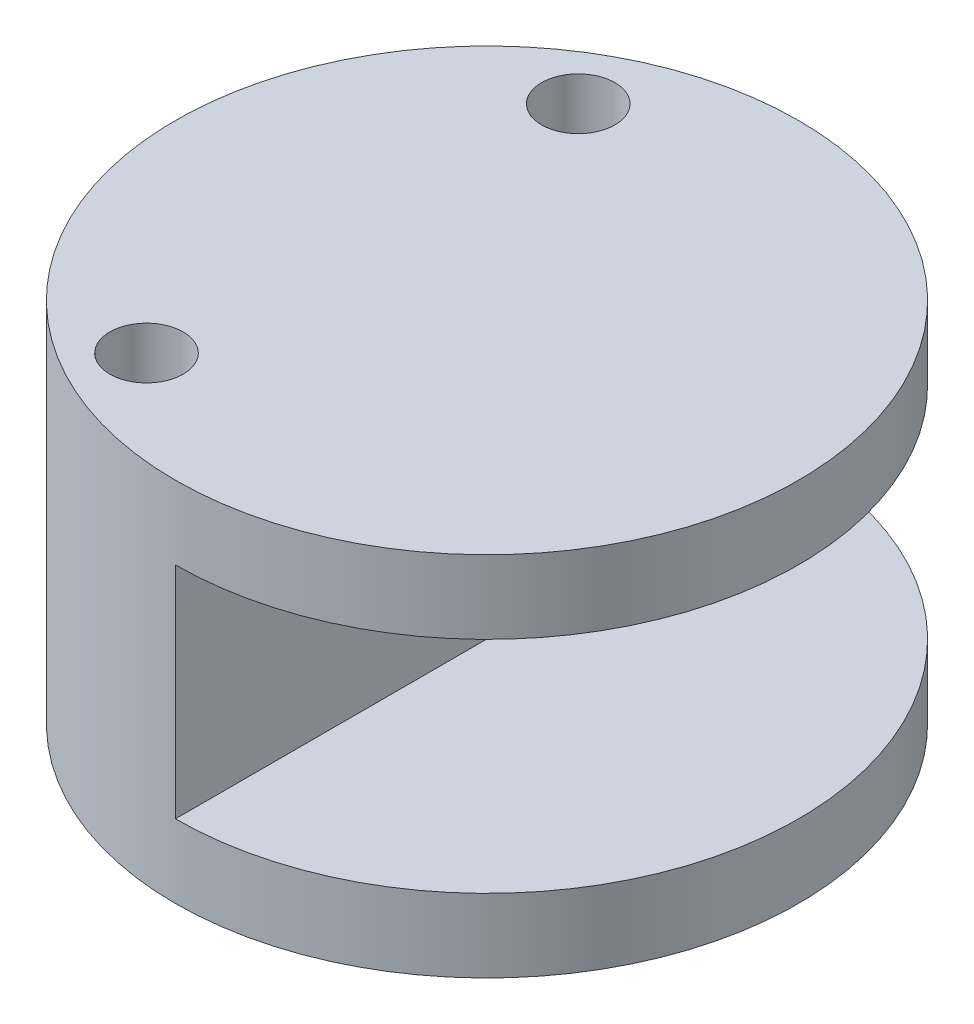
SolidWorks part; units mm, degrees
ref_plane "Front Plane" through (0, 0, 0) normal (0, 0, 1) x (1, 0, 0)
ref_plane "Top Plane" through (0, 0, 0) normal (0, 1, 0) x (1, 0, 0)
ref_plane "Right Plane" through (0, 0, 0) normal (1, 0, 0) x (0, 0, -1)
sketch "Sketch1" plane through (0, 0, 0) normal (0, 1, 0) x (1, 0, 0)
  circle A0 centre (0, 0) radius 12.7
  dimension "D1" = 25.4
sketch "Sketch2" plane through (0, 0, 0) normal (0, 1, 0) x (1, 0, 0)
  circle A0 centre (0, 0) radius 10.795
  dimension "D1" = 21.59
extrude "Boss-Extrude1" add sketch "Sketch2" against normal blind 12.7
sketch "Sketch3" plane through (0, 0, 0) normal (1, 0, 0) x (0, 0, -1)
  line L0 (12.7, 0) -> (-12.7, 0) construction
  line L1 (-13.6481, -2.54) -> (11.7912, -2.54)
  line L2 (-13.6481, -2.54) -> (-13.6481, -10.16)
  line L3 (-13.6481, -10.16) -> (11.7912, -10.16)
  line L4 (11.7912, -2.54) -> (11.7912, -10.16)
  dimension "D1" = 2.54
  dimension "D2" = 7.62
  dimension "D3" = 25.4393
extrude "Cut-Extrude1" cut sketch "Sketch3" along normal through all contours L4 L3 L2 L1
sketch "Sketch5" plane through (0, 0, 0) normal (0, 1, 0) x (1, 0, 0)
  line L0 (0, 0) -> (8.636, 0) construction
  line L1 (0, 0) -> (-4.318, -7.479) construction
  circle A0 centre (8.636, 0) radius 1.27
  circle A1 centre (-4.318, -7.479) radius 1.27
  circle A2 centre (-4.318, 7.479) radius 1.27
  dimension "D1" = 2.54
  dimension "D2" = 8.636
  dimension "D4" = 120
  dimension "D3" = 3
extrude "Cut-Extrude2" cut sketch "Sketch5" against normal blind 7.62 contours A1 | A2
equation "\"D1@Sketch7\" = \"D1@Sketch1\" / 10"
equation "\"D2@Sketch7\" = ( \"D1@Sketch1\" / 2 ) - ( \"D1@Sketch7\" * 1.6 )"
equation "\"D1@Sketch2\" = \"D1@Sketch1\" * 0.85"
equation "\"D2@Sketch3\" = \"D1@Boss-Extrude1\" * 3 / 5"
equation "\"D1@Sketch3\" = \"D1@Boss-Extrude1\" / 5"
equation "\"D1@Sketch5\" = ( \"D1@Sketch1\" / 10 )"
equation "\"D2@Sketch5\" = ( \"D1@Sketch1\" / 2 ) - ( \"D1@Sketch5\" * 1.6 )"
